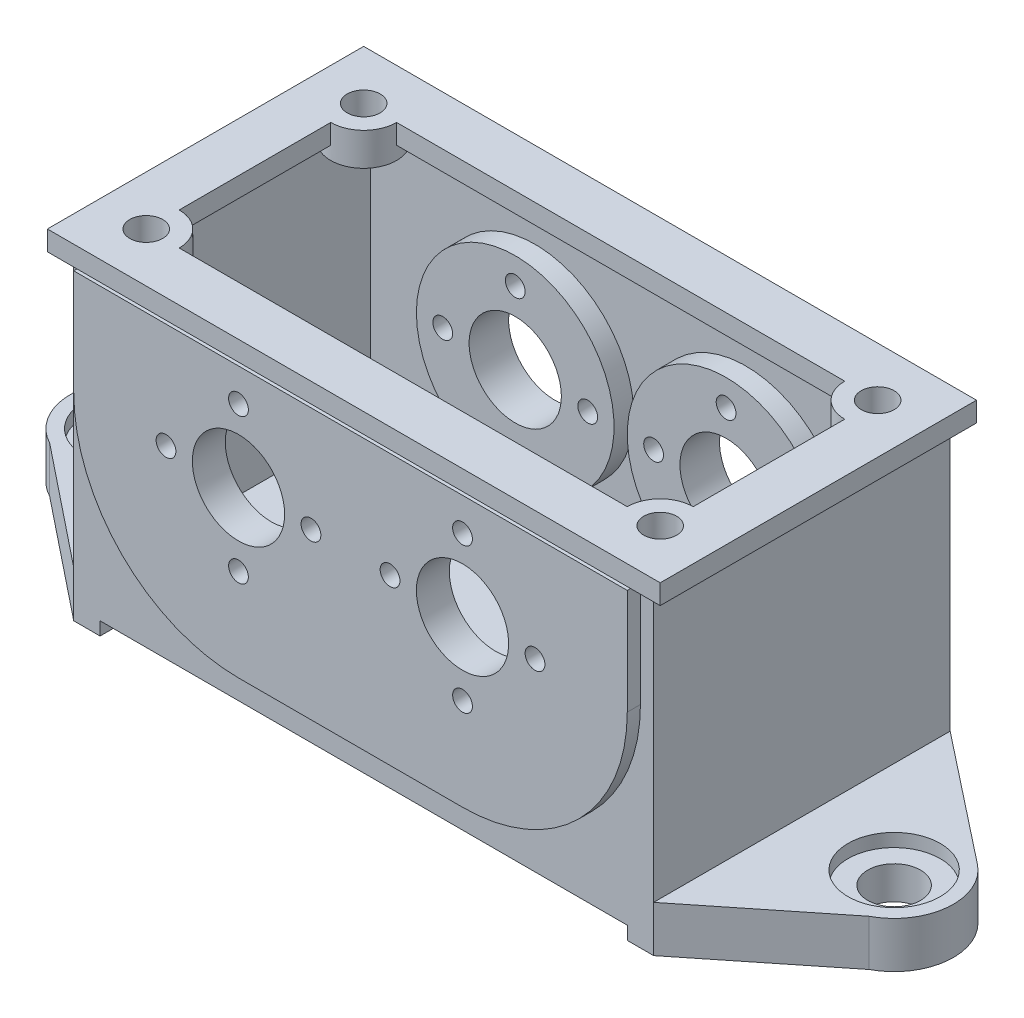
SolidWorks part; units mm, degrees
ref_plane "Front Plane" through (0, 0, 0) normal (0, 0, 1) x (1, 0, 0)
ref_plane "Top Plane" through (0, 0, 0) normal (0, 1, 0) x (1, 0, 0)
ref_plane "Right Plane" through (0, 0, 0) normal (1, 0, 0) x (0, 0, -1)
sketch "Sketch9" plane through (0, 0, 0) normal (0, 1, 0) x (1, 0, 0)
  line L1 (-44, 22.5) -> (44, 22.5)
  line L3 (-44, -22.5) -> (44, -22.5)
  line L5 (-44, 22.5) -> (-63.5725, 7.0673)
  line L6 (-44, -22.5) -> (-62.1815, -7.9697)
  line L7 (44, 22.5) -> (63.5725, 7.0673)
  line L8 (44, -22.5) -> (62.1815, -7.9697)
  arc A0 (-63.5725, 7.0673) -> (-62.1815, -7.9697) centre (-58, 0) ccw
  arc A1 (63.5725, 7.0673) -> (62.1815, -7.9697) centre (58, 0) cw
  dimension "D1" = 88
  dimension "D2" = 45
extrude "Boss-Extrude5" add sketch "Sketch9" along normal blind 7
sketch "Sketch10" plane through (0, 7, 0) normal (0, 1, 0) x (1, 0, 0)
  line L0 (44, 22.5) -> (-44, 22.5) construction
  line L1 (-44, -22.5) -> (44, -22.5)
  line L2 (-44, -22.5) -> (-44, 22.5)
  line L3 (-44, 22.5) -> (44, 22.5)
  line L4 (44, -22.5) -> (44, 22.5)
  line L7 (-41, 19.5) -> (41, 19.5)
  line L8 (-41, 19.5) -> (-41, -19.5)
  line L9 (-41, -19.5) -> (41, -19.5)
  line L10 (41, 19.5) -> (41, -19.5)
  point P0 (0, 0)
  point P7 (0, 0)
  dimension "D1" = 3
  dimension "D2" = 3
  dimension "D3" = 3
  dimension "D4" = 3
  dimension "D5" = 19.5725
  dimension "D6" = 104.5725
  dimension "D7" = 42
extrude "Boss-Extrude6" add sketch "Sketch10" along normal blind 41
sketch "Sketch11" plane through (0, 48, 0) normal (0, 1, 0) x (1, 0, 0)
  line L0 (44, -22.5) -> (44, 22.5) construction
  line L1 (-46.5, 24) -> (46.5, 24)
  line L2 (-46.5, 24) -> (-46.5, -24)
  line L3 (-46.5, -24) -> (46.5, -24)
  line L4 (46.5, 24) -> (46.5, -24)
  line L5 (-39, 16.5) -> (39, 16.5)
  line L6 (-39, 16.5) -> (-39, -16.5)
  line L7 (-39, -16.5) -> (39, -16.5)
  line L8 (39, 16.5) -> (39, -16.5)
  line L9 (44, 22.5) -> (-44, 22.5) construction
  point P0 (0, 0)
  point P6 (0, 0)
  dimension "D1" = 93
  dimension "D2" = 48
  dimension "D3" = 7.5
  dimension "D4" = 46.5
  dimension "D5" = 7.5
  dimension "D6" = 7.5
  dimension "D7" = 83
  dimension "D8" = 6
extrude "Boss-Extrude7" add sketch "Sketch11" along normal blind 3
sketch "Sketch12" plane through (0, 51, 0) normal (0, 1, 0) x (1, 0, 0)
  line L0 (46.5, -24) -> (46.5, 24) construction
  line L2 (46.5, 24) -> (-46.5, 24) construction
  circle A0 centre (39, 16.5) radius 5
  circle A1 centre (39, -16.5) radius 5
  circle A2 centre (-39, -16.5) radius 5
  circle A3 centre (-39, 16.5) radius 5
  dimension "D1" = 10
  dimension "D2" = 10
  dimension "D3" = 10
  dimension "D4" = 10
  dimension "D5" = 7.5
  dimension "D6" = 85.5
  dimension "D7" = 7.5
  dimension "D8" = 40.5
extrude "Boss-Extrude8" add sketch "Sketch12" against normal blind 5 contours A1 | A0 | A2 | A3
sketch "Sketch13" plane through (0, 51, 0) normal (0, 1, 0) x (1, 0, 0)
  line L0 (39, -11.5) -> (39, 11.5) construction
  line L2 (34, 16.5) -> (-34, 16.5) construction
  circle A0 centre (39, 16.5) radius 2.5
  circle A1 centre (39, -16.5) radius 2.5
  circle A2 centre (-39, 16.5) radius 2.5
  circle A3 centre (-39, -16.5) radius 2.5
  dimension "D1" = 5
  dimension "D2" = 5
  dimension "D3" = 5
  dimension "D4" = 5
  dimension "D5" = 5
  dimension "D6" = 78
  dimension "D7" = 5
  dimension "D8" = 33
  dimension "D9" = 5
  dimension "D10" = 5
extrude "Cut-Extrude1" cut sketch "Sketch13" against normal blind 5 contours A2 | A0 | A1 | A3
sketch "Sketch14" plane through (0, 0, -19.5) normal (0, 0, 1) x (1, 0, 0)
  line L0 (-41, 46) -> (-41, 7) construction
  line L2 (35, 48) -> (-35, 48) construction
  circle A0 centre (16, 27.5) radius 15
  circle A3 centre (-16, 27.5) radius 15
  dimension "D2" = 30
  dimension "D3" = 25
  dimension "D4" = 57
  dimension "D1" = 30
  dimension "D5" = 76
  dimension "D6" = 2
  dimension "D7" = 20.5
extrude "Boss-Extrude9" add sketch "Sketch14" along normal blind 3
sketch "Sketch16" plane through (0, 0, -16.5) normal (0, 0, 1) x (1, 0, 0)
  circle A0 centre (-16, 27.5) radius 7
  circle A1 centre (16, 27.5) radius 7
  circle A4 centre (-16, 27.5) radius 15 construction
  dimension "D2" = 14
  dimension "D1" = 14
  dimension "D3" = 32
extrude "Cut-Extrude2" cut sketch "Sketch16" against normal blind 22
sketch "Sketch17" plane through (0, 0, -16.5) normal (0, 0, 1) x (1, 0, 0)
  circle A1 centre (16, 38.5) radius 1.5
  circle A2 centre (27, 27.5) radius 1.5
  circle A3 centre (16, 16.5) radius 1.5
  circle A4 centre (5, 27.5) radius 1.5
  circle A5 centre (16, 27.5) radius 7 construction
  circle A6 centre (-5, 27.5) radius 1.5
  circle A7 centre (-16, 16.5) radius 1.5
  circle A8 centre (-27, 27.5) radius 1.5
  circle A9 centre (-16, 38.5) radius 1.5
  point P24 (16, 27.5)
  dimension "D2" = 11
  dimension "D3" = 3
  dimension "D5" = 11
  dimension "D6" = 11
  dimension "D4" = 4
extrude "Cut-Extrude3" cut sketch "Sketch17" against normal blind 22
sketch "Sketch18" plane through (0, 0, 22.5) normal (0, 0, 1) x (1, 0, 0)
  line L0 (-44, 0) -> (44, 0) construction
  line L3 (-40, 2) -> (40, 2)
  line L5 (-40, 2) -> (-40, 0)
  line L6 (40, 2) -> (40, 0)
  line L7 (-40, 0) -> (40, 0)
  line L8 (44, 7) -> (44, 0) construction
  line L9 (-44, 7) -> (-44, 0) construction
  point P0 (0, 0)
  dimension "D1" = 2
  dimension "D2" = 4
  dimension "D3" = 4
extrude "Cut-Extrude4" cut sketch "Sketch18" against normal blind 92 contours L3 L6 L7 L5
sketch "Sketch19" plane through (0, 0, 22.5) normal (0, 0, 1) x (1, 0, 0)
  line L0 (-42, 48) -> (42, 48)
  line L5 (-42, 48) -> (-42, 32)
  line L6 (42, 48) -> (42, 32)
  line L7 (-17, 7) -> (17, 7)
  line L10 (40, 2) -> (40, 0) construction
  line L11 (40, 0) -> (44, 0) construction
  arc A0 (-17, 7) -> (-42, 32) centre (-17, 32) cw
  arc A1 (42, 32) -> (17, 7) centre (17, 32) cw
  dimension "D3" = 25
  dimension "D4" = 25
  dimension "D5" = 4
  dimension "D6" = 2
  dimension "D7" = 7
extrude "Boss-Extrude11" add sketch "Sketch19" along normal blind 2 contours L0 L6 A1 L7 A0 L5
sketch "Sketch20" plane through (0, 0, 24.5) normal (0, 0, 1) x (1, 0, 0)
  line L0 (-42, 48) -> (-42, 32) construction
  line L3 (-17, 7) -> (17, 7) construction
  circle A0 centre (-17, 32) radius 7
  circle A1 centre (17, 32) radius 7
  dimension "D1" = 14
  dimension "D2" = 14
  dimension "D3" = 59
  dimension "D4" = 25
  dimension "D5" = 41
  dimension "D6" = 17
extrude "Cut-Extrude5" cut sketch "Sketch20" against normal blind 14
sketch "Sketch21" plane through (0, 0, 24.5) normal (0, 0, 1) x (1, 0, 0)
  circle A1 centre (-17, 43) radius 1.5
  circle A2 centre (-6, 32) radius 1.5
  circle A3 centre (-17, 21) radius 1.5
  circle A4 centre (-28, 32) radius 1.5
  circle A5 centre (17, 21) radius 1.5
  circle A6 centre (28, 32) radius 1.5
  circle A7 centre (17, 43) radius 1.5
  circle A8 centre (6, 32) radius 1.5
  point P20 (-17, 32)
  dimension "D2" = 3
  dimension "D3" = 4
extrude "Cut-Extrude6" cut sketch "Sketch21" against normal blind 14 contours A6 | A5 | A2 | A1 | A7 | A8 | A3 | A4
sketch "Sketch22" plane through (0, 7, 0) normal (0, 1, 0) x (1, 0, 0)
  circle A0 centre (-58, 0) radius 4
  circle A1 centre (58, 0) radius 4
  dimension "D1" = 8
extrude "Cut-Extrude8" cut sketch "Sketch22" against normal blind 14 contours A1 | A0
sketch "Sketch23" plane through (0, 7, 0) normal (0, 1, 0) x (1, 0, 0)
  circle A0 centre (-58, 0) radius 7
  circle A1 centre (58, 0) radius 7
  dimension "D1" = 14
extrude "Cut-Extrude9" cut sketch "Sketch23" against normal blind 2
